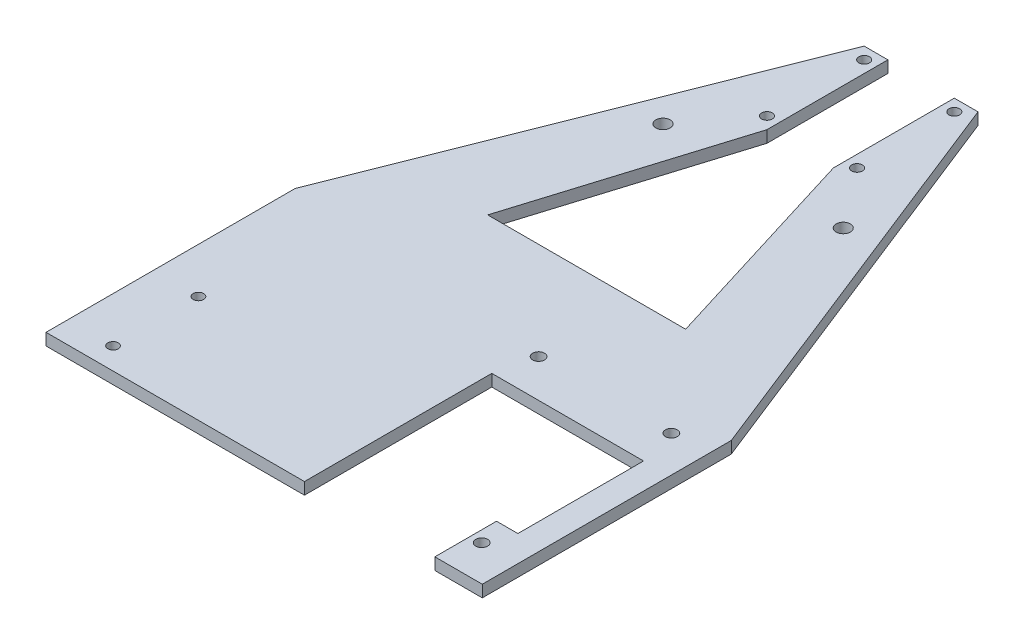
SolidWorks part; units mm, degrees
material "Maple"
ref_plane "Front Plane" through (0, 0, 0) normal (0, 0, 1) x (1, 0, 0)
ref_plane "Top Plane" through (0, 0, 0) normal (0, 1, 0) x (1, 0, 0)
ref_plane "Right Plane" through (0, 0, 0) normal (1, 0, 0) x (0, 0, -1)
sketch "Sketch1" plane through (0, 0, 0) normal (0, 1, 0) x (1, 0, 0)
  line L1 (-91.7221, -4.6536) -> (-91.7221, 90.3464)
  line L2 (-91.7221, 90.3464) -> (-23.7221, 262.3958)
  line L3 (92.2779, -4.6536) -> (92.2779, 90.3464)
  line L4 (92.2779, 90.3464) -> (24.2779, 262.3958)
  line L5 (92.2779, -4.6536) -> (92.2779, 121.3464) construction
  line L6 (92.2779, 121.3464) -> (-112.921, 121.3464) construction
  line L12 (-57.7221, 176.3711) -> (-24.8562, 163.3813) construction
  line L13 (58.2779, 176.3711) -> (25.4119, 163.3813) construction
  line L14 (15.6163, 265.7822) -> (-65.3286, 60.9804) construction
  line L15 (-16.7848, 270.1448) -> (67.6086, 56.6178) construction
  line L20 (42.0255, 121.3464) -> (-41.4698, 121.3464)
  line L21 (92.2779, -4.6536) -> (72.2779, -4.6536) construction
  line L22 (72.2779, -4.6536) -> (72.2779, 11.3464)
  line L23 (72.2779, 11.3464) -> (81.2779, 11.3464)
  line L24 (81.2779, 11.3464) -> (81.2779, 64.3464)
  line L25 (81.2779, 64.3464) -> (17.2778, 64.3464)
  line L26 (17.2778, 64.3464) -> (17.2778, -4.6536)
  line L29 (72.2779, -4.6536) -> (77.0104, -4.6536) construction
  line L30 (77.0104, -4.6536) -> (77.0104, 0.3464) construction
  line L31 (77.0104, 0.3464) -> (77.0104, 80.3464) construction
  line L32 (77.0104, 80.3464) -> (21.0104, 80.3464) construction
  line L33 (-23.7221, 262.3958) -> (-13.7221, 262.3958)
  line L34 (-13.7221, 262.3958) -> (-13.7221, 211.3958)
  line L36 (24.2779, 262.3958) -> (14.2779, 262.3958)
  line L37 (14.2779, 262.3958) -> (14.2779, 211.3958)
  line L39 (77.0104, 0.3464) -> (-72.6567, 0.3464) construction
  line L40 (-72.6567, 0.3464) -> (-72.6567, 37.6589) construction
  line L41 (-18.7221, 262.3958) -> (-18.7221, 216.3958) construction
  line L42 (-18.7221, 262.3958) -> (-18.7221, 257.3958) construction
  line L43 (19.2779, 262.3958) -> (19.2779, 216.3958) construction
  line L44 (19.2779, 262.3958) -> (19.2779, 257.3958) construction
  line L45 (-91.7221, -4.6536) -> (-91.7221, -10.4336)
  line L47 (17.2778, -10.4336) -> (17.2778, -4.6536)
  line L48 (-13.7221, 191.5519) -> (-37.7221, 191.5519) construction
  line L49 (14.2779, 191.5519) -> (38.2779, 191.5519) construction
  line L50 (72.2779, -4.6536) -> (72.2779, -10.4336)
  line L52 (92.2779, -10.4336) -> (92.2779, -4.6536)
  line L53 (-72.6567, 0.3464) -> (-72.6567, -5.4506) construction
  line L54 (-72.6567, 37.6589) -> (-72.6567, 30.5494) construction
  line L56 (-94.6567, -14.6683) -> (-88.2567, -14.6683) construction
  line L57 (-91.4567, -14.6683) -> (17.2778, -14.6683)
  line L58 (17.2778, -14.6683) -> (17.2778, -10.4336)
  line L59 (72.2779, -10.4336) -> (72.2779, -14.6683)
  line L60 (72.2779, -14.6683) -> (92.2779, -14.6683)
  line L61 (92.2779, -14.6683) -> (92.2779, -10.4336)
  line L62 (42.0255, 121.3464) -> (14.2779, 211.3958)
  line L63 (-41.4698, 121.3464) -> (-13.7221, 211.3958)
  line L64 (-91.7221, -10.4336) -> (-91.7221, -14.6683)
  line L65 (-91.7221, -14.6683) -> (-91.4567, -14.6683)
  circle A0 centre (77.0104, 0.3464) radius 2.5
  circle A1 centre (77.0104, 80.3464) radius 2.5
  circle A2 centre (21.0104, 80.3464) radius 2.5
  circle A5 centre (-18.7221, 257.3958) radius 2.25
  circle A6 centre (-18.7221, 216.3958) radius 2.25
  circle A7 centre (19.2779, 257.3958) radius 2.25
  circle A8 centre (19.2779, 216.3958) radius 2.25
  circle A9 centre (-37.7221, 191.5519) radius 3
  circle A10 centre (38.2779, 191.5519) radius 3
  circle A11 centre (-72.6567, -5.4506) radius 2.2
  circle A12 centre (-72.6567, 30.5494) radius 2.2
  point P4 (0, 0)
  point P17 (-24.8562, 163.3813)
  point P19 (25.4119, 163.3813)
  dimension "D1" = 5
  dimension "D2" = 36
  dimension "D4" = 184
  dimension "D5" = 28
  dimension "D6" = 48
  dimension "D7" = 80
  dimension "D8" = 15.2674
extrude "Boss-Extrude1" add sketch "Sketch1" along normal blind 5
